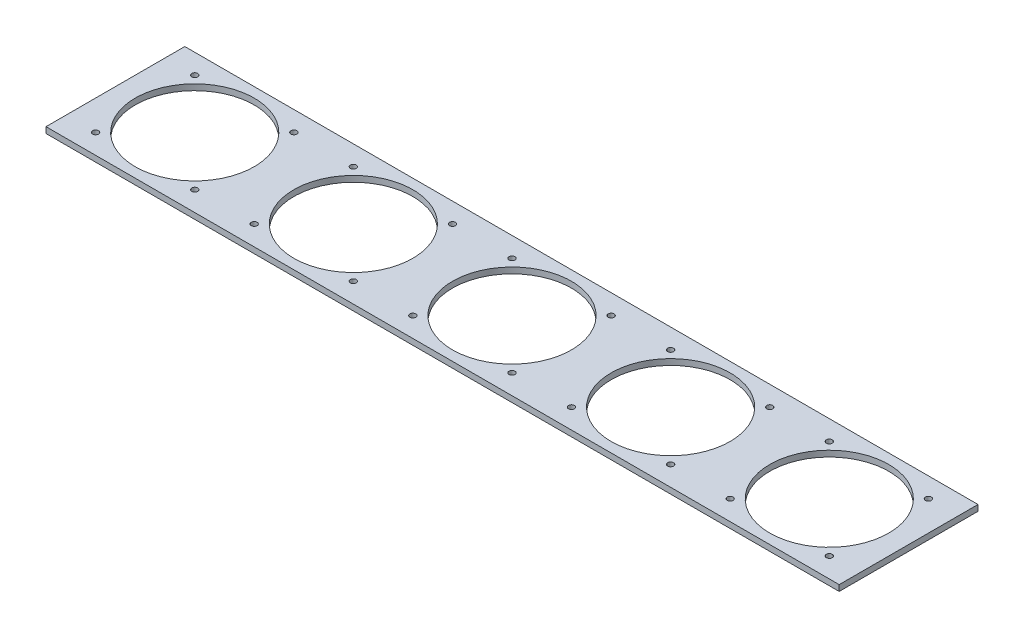
SolidWorks part; units mm, degrees
ref_plane "Ön Düzlem" through (0, 0, 0) normal (0, 0, 1) x (1, 0, 0)
ref_plane "Üst Düzlem" through (0, 0, 0) normal (0, 1, 0) x (1, 0, 0)
ref_plane "Sağ Düzlem" through (0, 0, 0) normal (1, 0, 0) x (0, 0, -1)
sketch "Sketch1" plane through (0, 0, 0) normal (0, 1, 0) x (1, 0, 0)
  line L0 (0, 35) -> (400, 35) construction
  line L1 (0, 0) -> (400, 0)
  line L2 (0, 0) -> (0, 70)
  line L3 (0, 70) -> (400, 70)
  line L4 (400, 0) -> (400, 70)
  line L5 (40, 35) -> (40, 5) construction
  circle A0 centre (40, 35) radius 30
  circle A1 centre (120, 35) radius 30
  circle A2 centre (200, 35) radius 30
  circle A3 centre (280, 35) radius 30
  circle A4 centre (360, 35) radius 30
  circle A5 centre (15, 60) radius 1.5
  circle A6 centre (65, 60) radius 1.5
  circle A7 centre (65, 10) radius 1.5
  circle A8 centre (15, 10) radius 1.5
  circle A9 centre (95, 60) radius 1.5
  circle A10 centre (145, 60) radius 1.5
  circle A11 centre (145, 10) radius 1.5
  circle A12 centre (95, 10) radius 1.5
  circle A13 centre (175, 60) radius 1.5
  circle A14 centre (225, 60) radius 1.5
  circle A15 centre (225, 10) radius 1.5
  circle A16 centre (175, 10) radius 1.5
  circle A17 centre (255, 60) radius 1.5
  circle A18 centre (305, 60) radius 1.5
  circle A19 centre (305, 10) radius 1.5
  circle A20 centre (255, 10) radius 1.5
  circle A21 centre (335, 60) radius 1.5
  circle A22 centre (385, 60) radius 1.5
  circle A23 centre (385, 10) radius 1.5
  circle A24 centre (335, 10) radius 1.5
  dimension "D4" = 60
  dimension "D7" = 3
  dimension "D1" = 70
  dimension "D2" = 400
  dimension "D3" = 40
  dimension "D6" = 160
  dimension "D8" = 50
  dimension "D9" = 50
  dimension "D5" = 5
  dimension "D10" = 5
extrude "Boss-Extrude1" add sketch "Sketch1" along normal blind 3
